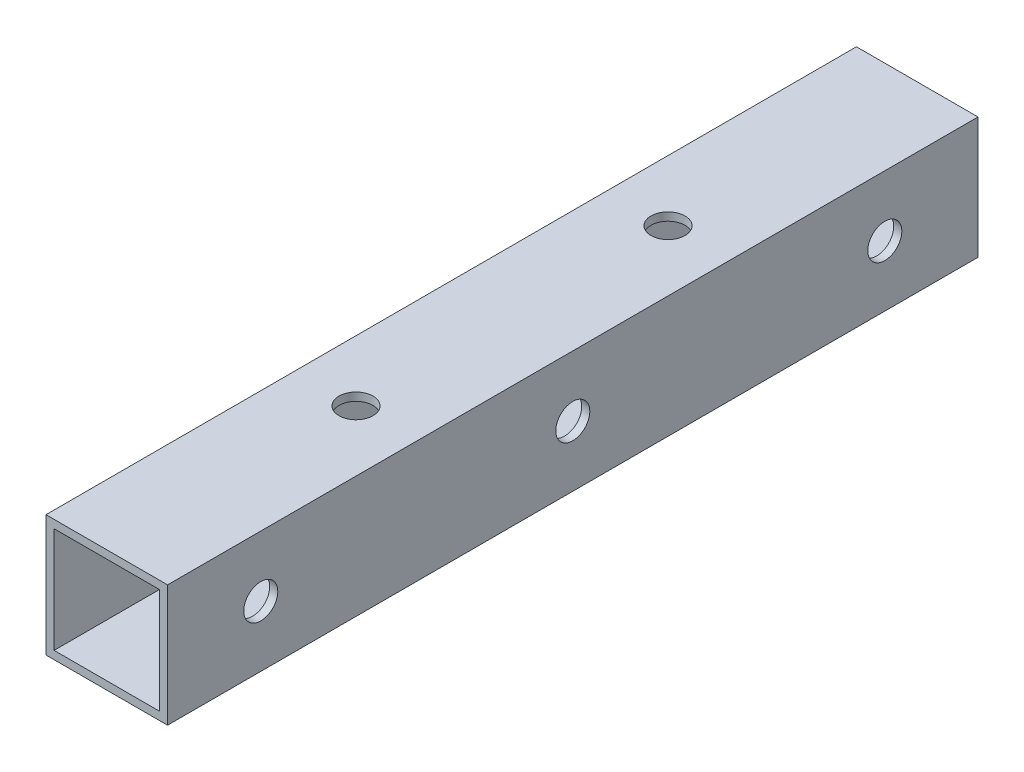
SolidWorks part; units mm, degrees
ref_plane "前视基准面" through (0, 0, 0) normal (0, 0, 1) x (1, 0, 0)
ref_plane "上视基准面" through (0, 0, 0) normal (0, 1, 0) x (1, 0, 0)
ref_plane "右视基准面" through (0, 0, 0) normal (1, 0, 0) x (0, 0, -1)
other "Configuration Table"
sketch "草图1" plane through (0, 0, 0) normal (0, 0, 1) x (1, 0, 0)
  line L1 (-7.5, 7.5) -> (7.5, 7.5)
  line L2 (-7.5, 7.5) -> (-7.5, -7.5)
  line L3 (-7.5, -7.5) -> (7.5, -7.5)
  line L4 (7.5, 7.5) -> (7.5, -7.5)
  line L5 (-7.5, 7.5) -> (7.5, -7.5) construction
  line L6 (-7.5, -7.5) -> (7.5, 7.5) construction
  line L7 (-6.5, 6.5) -> (6.5, 6.5)
  line L8 (-6.5, 6.5) -> (-6.5, -6.5)
  line L9 (-6.5, -6.5) -> (6.5, -6.5)
  line L10 (6.5, 6.5) -> (6.5, -6.5)
  line L11 (-6.5, 6.5) -> (6.5, -6.5) construction
  line L12 (-6.5, -6.5) -> (6.5, 6.5) construction
  point P0 (0, 0)
  point P5 (0, 0)
  dimension "D1" = 15
  dimension "D2" = 15
  dimension "D3" = 1
  dimension "D4" = 1
extrude "凸台-拉伸1" add sketch "草图1" along normal blind 100
sketch "草图2" plane through (7.5, 0, 0) normal (1, 0, 0) x (0, 0, -1)
  line L0 (-100, 0) -> (0, 0) construction
  line L1 (-100, -7.5) -> (-100, 7.5) construction
  line L2 (-50, 7.5) -> (-50, -7.5) construction
  line L3 (-100, 7.5) -> (0, 7.5) construction
  line L4 (-100, -7.5) -> (0, -7.5) construction
  circle A0 centre (-50, 0) radius 2.1
  circle A1 centre (-88.5, 0) radius 2.1
  circle A2 centre (-11.5, 0) radius 2.1
  dimension "D1" = 4.2
  dimension "D2" = 77
  dimension "D3" = 4.2
extrude "切除-拉伸1" cut sketch "草图2" against normal blind 366
sketch "草图3" plane through (0, 7.5, 0) normal (0, 1, 0) x (1, 0, 0)
  line L0 (0, 0) -> (0, -100) construction
  line L1 (7.5, -100) -> (-7.5, -100) construction
  line L2 (-7.5, -50) -> (7.5, -50) construction
  line L3 (-7.5, -100) -> (-7.5, 0) construction
  line L4 (7.5, -100) -> (7.5, 0) construction
  circle A0 centre (0, -30.75) radius 2.1
  circle A1 centre (0, -69.25) radius 2.1
  dimension "D1" = 38.5
  dimension "D2" = 4.2
extrude "切除-拉伸2" cut sketch "草图3" against normal blind 55
